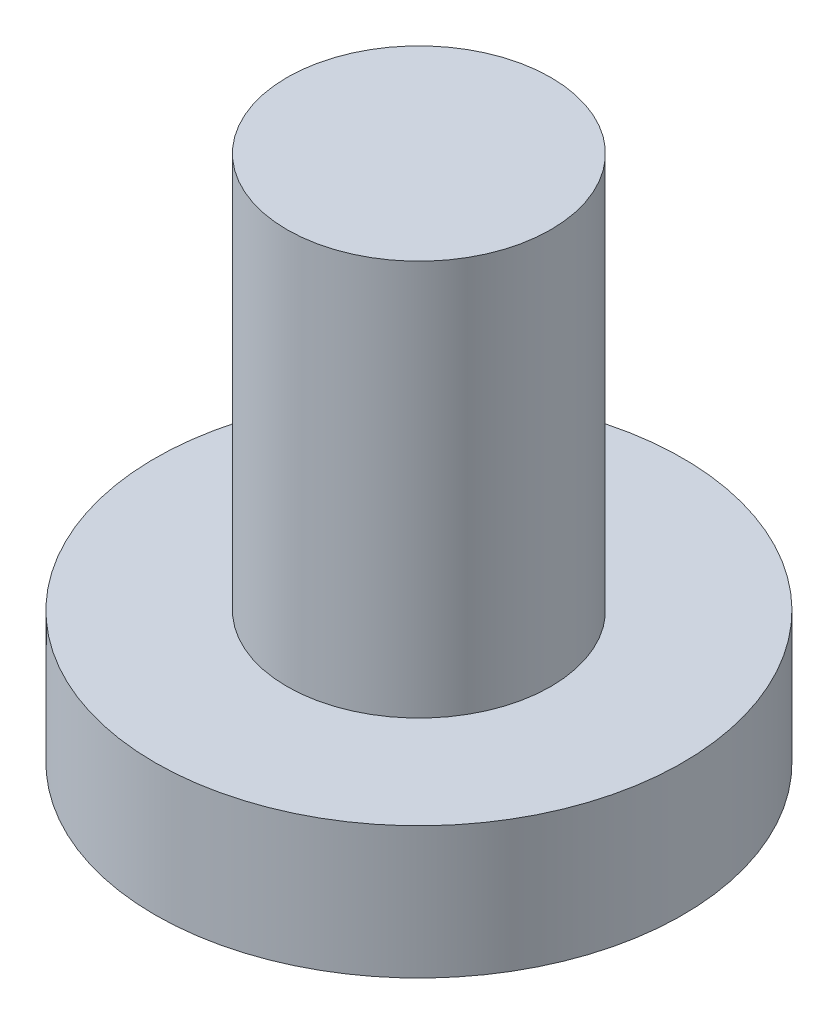
SolidWorks part; units mm, degrees
ref_plane "Front Plane" through (0, 0, 0) normal (0, 0, 1) x (1, 0, 0)
ref_plane "Top Plane" through (0, 0, 0) normal (0, 1, 0) x (1, 0, 0)
ref_plane "Right Plane" through (0, 0, 0) normal (1, 0, 0) x (0, 0, -1)
sketch "Sketch1" plane through (0, 0, 0) normal (0, 1, 0) x (1, 0, 0)
  circle A0 centre (0, 0) radius 4
  dimension "D1" = 8
extrude "Boss-Extrude1" add sketch "Sketch1" along normal blind 2
sketch "Sketch2" plane through (0, 2, 0) normal (0, 1, 0) x (1, 0, 0)
  circle A0 centre (0, 0) radius 2
  dimension "D1" = 4
extrude "Boss-Extrude2" add sketch "Sketch2" along normal blind 6
sketch "Sketch5" plane through (0, 0, 0) normal (0, -1, 0) x (1, 0, 0)
  circle A0 centre (0, 0) radius 4
